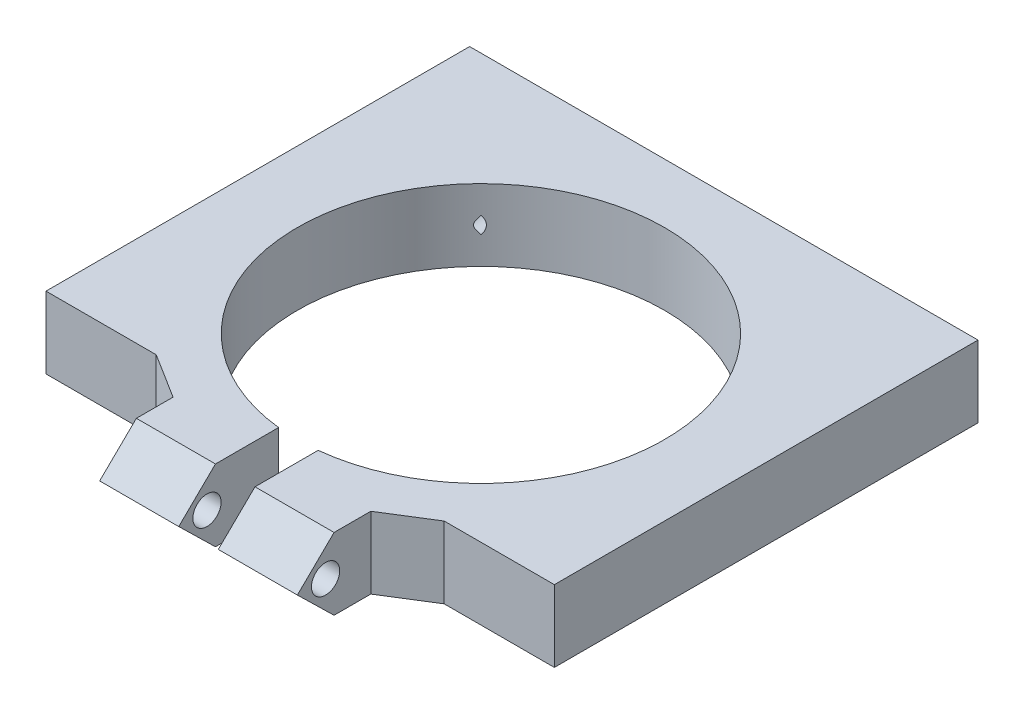
SolidWorks part; units mm, degrees
ref_plane "Plano frontal" through (0, 0, 0) normal (0, 0, 1) x (1, 0, 0)
ref_plane "Plano superior" through (0, 0, 0) normal (0, 1, 0) x (1, 0, 0)
ref_plane "Plano direito" through (0, 0, 0) normal (1, 0, 0) x (0, 0, -1)
sketch "Esboço1" plane through (0, 0, 0) normal (0, 1, 0) x (1, 0, 0)
  line L0 (45, 46.5) -> (-45, -46.5) construction
  line L1 (-45, 46.5) -> (45, 46.5)
  line L2 (-45, 46.5) -> (-45, -46.5)
  line L3 (-45, -46.5) -> (45, -46.5)
  line L4 (45, 46.5) -> (45, -46.5)
  dimension "D1" = 90
  dimension "D2" = 93
extrude "Ressalto-extrusão1" add sketch "Esboço1" along normal blind 12.7 contours L2 L3 L4 L1
sketch "Esboço3" plane through (0, 12.7, 0) normal (0, 1, 0) x (1, 0, 0)
  line L0 (-45, -46.5) -> (45, -46.5) construction
  line L1 (45, 46.5) -> (45, -46.5) construction
  circle A0 centre (0, 3.5) radius 32.51
  dimension "D1" = 65.02
  dimension "D2" = 50
  dimension "D3" = 45
extrude "Corte-extrusão2" cut sketch "Esboço3" against normal through all
sketch "Esboço5" plane through (0, 12.7, 0) normal (0, 1, 0) x (1, 0, 0)
  line L0 (0, -46.5) -> (0, -37.4552) construction
  line L1 (45, -46.5) -> (17.5, -46.5)
  line L2 (45, -46.5) -> (45, -33.5)
  line L3 (45, -33.5) -> (17.5, -33.5)
  line L4 (17.5, -46.5) -> (17.5, -33.5)
  line L5 (-45, -46.5) -> (-17.5, -46.5)
  line L6 (-45, -46.5) -> (-45, -33.5)
  line L7 (-45, -33.5) -> (-17.5, -33.5)
  line L8 (-17.5, -46.5) -> (-17.5, -33.5)
  line L9 (-45, -46.5) -> (45, -46.5) construction
  dimension "D1" = 17.5
  dimension "D2" = 17.5
  dimension "D3" = 13
  dimension "D4" = 13
extrude "Corte-extrusão4" cut sketch "Esboço5" against normal up to next
sketch "Esboço6" plane through (0, 12.7, 0) normal (0, 1, 0) x (1, 0, 0)
  line L1 (0, 0) -> (0, -46.5) construction
  line L2 (-17.5, -46.5) -> (17.5, -46.5) construction
  line L4 (3.5, -46.5) -> (-3.5, -46.5)
  line L5 (3.5, -46.5) -> (3.5, -20.1703)
  line L6 (3.5, -20.1703) -> (-3.5, -20.1703)
  line L7 (-3.5, -46.5) -> (-3.5, -20.1703)
  dimension "D1" = 3.5
  dimension "D2" = 3.5
extrude "Corte-extrusão5" cut sketch "Esboço6" against normal up to next
sketch "Esboço7" plane through (-17.5, 0, 0) normal (-1, 0, 0) x (0, 0, 1)
  line L0 (46.5, 12.7) -> (36.5, 0) construction
  line L1 (46.5, 0) -> (33.5, 0) construction
  circle A0 centre (41.5, 6.35) radius 2.5
  dimension "D2" = 5
  dimension "D1" = 10
extrude "Corte-extrusão6" cut sketch "Esboço7" against normal up to surface (35 mm away) up to face at (17.5, 6.35, 40)
sketch "Esboço8" plane through (-17.5, 0, 0) normal (-1, 0, 0) x (0, 0, 1)
  line L0 (41.5, 6.35) -> (46.5, 6.35) construction
  line L1 (46.5, 0) -> (46.5, 12.7) construction
  line L2 (40, 12.7) -> (46.5, 6.35)
  line L3 (46.5, 12.7) -> (33.5, 12.7) construction
  line L4 (46.5, 0) -> (46.5, 12.7)
  line L5 (46.5, 12.7) -> (40, 12.7)
  line L6 (46.5, 0) -> (40, 0)
  line L7 (40, 0) -> (46.5, 6.35)
  line M2 (46.5, 0) -> (46.5, 12.7)
  line M3 (46.5, 12.7) -> (33.5, 12.7)
  line M5 (33.5, 0) -> (46.5, 0)
extrude "Corte-extrusão7" cut sketch "Esboço8" against normal up to surface (35 mm away) contours L2 M3 M2 | L7 M5 M2 up to face at (17.5, 6.35, 44)
sketch "Esboço9" plane through (0, 12.7, 0) normal (0, 1, 0) x (-1, 0, 0)
  line L0 (0, 0) -> (0, 41.0123) construction
  line L1 (45, -46.5) -> (45, 33.5) construction
  line L2 (45, 28.5) -> (25.5, 28.5)
  line L3 (45, 28.5) -> (45, 33.5)
  line L4 (45, 33.5) -> (25.5, 33.5)
  line L6 (17.5, 33.5) -> (45, 33.5) construction
  line L8 (3.5, 46.5) -> (17.5, 46.5) construction
  line L10 (-45, 33.5) -> (-25.5, 33.5)
  line L11 (-45, 28.5) -> (-45, 33.5)
  line L12 (-45, 28.5) -> (-25.5, 28.5)
  line L13 (25.5, 28.5) -> (17.5, 33.5)
  line L14 (17.5, 33.5) -> (25.5, 33.5)
  line L15 (-25.5, 28.5) -> (-17.5, 33.5)
  line L16 (-17.5, 33.5) -> (-25.5, 33.5)
  dimension "D2" = 18
extrude "Corte-extrusão8" cut sketch "Esboço9" against normal through all
hole_wizard "Taladro de margen para #00001" positions "Croquis2" profile "Croquis1" hole size "#0000" standard "Pulgada Ansi"
sketch "Croquis2" plane through (0, 0, -46.5) normal (0, 0, -1) x (-1, 0, 0)
  line L0 (-45, 12.7) -> (-45, 0) construction
  line L1 (45, 12.7) -> (45, 0) construction
  point P1 (-40, 6.35)
  point P4 (-25, 6.35)
  point P7 (40, 6.35)
  point P10 (25, 6.35)
  point P15 (-45, 6.35)
  dimension "D1" = 5
  dimension "D2" = 20
  dimension "D3" = 20
  dimension "D4" = 5
sketch "Croquis1" plane through (40, 6.35, -46.5) normal (1, 0, 0) x (0, 1, 0)
  line L0 (0, 0) -> (0, 21.5022)
  line L1 (0, 21.5022) -> (2.5, 20)
  line L2 (2.5, 20) -> (2.5, 0)
  line L5 (2.5, 0) -> (0, 0)
  line L10 (0, 21.5022) -> (-2.5, 20) construction
  line L11 (0, -6.35) -> (0, 107.95) construction
  dimension "Diámetro de taladro" = 5
  dimension "Profundidad de taladro" = 20
  dimension "Ángulo de perforador" = 118
sketch "Croquis3" plane through (0, 12.7, 0) normal (0, 1, 0) x (1, 0, 0)
  line L0 (0, 36.01) -> (32.51, 36.01)
  line L1 (32.51, 36.01) -> (32.51, 46.5)
  line L2 (-45, 46.5) -> (45, 46.5) construction
  line L3 (32.51, 46.5) -> (0, 46.5)
  line L4 (0, 46.5) -> (0, 36.01)
  line L5 (-17.5, -46.5) -> (17.5, -46.5) construction
  line L6 (0, -29.01) -> (0, -33.7251) construction
  arc A0 (3.5, -28.821) -> (-3.5, -28.821) centre (0, 3.5) ccw construction
  circle A1 centre (0, 3.5) radius 32.51
  dimension "D1" = 10.49
  dimension "D2" = 17.49
